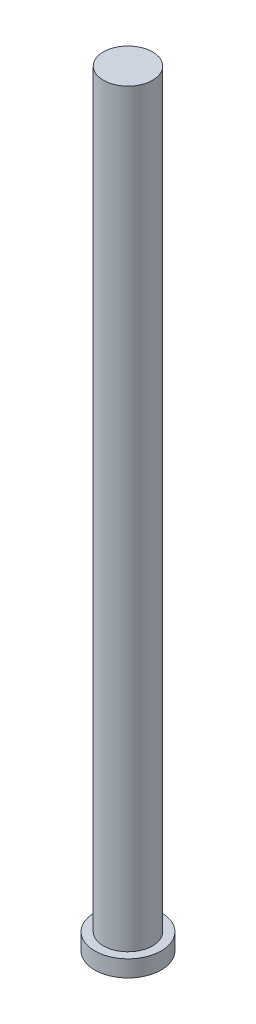
SolidWorks part; units mm, degrees
ref_plane "Front Plane" through (0, 0, 0) normal (0, 0, 1) x (1, 0, 0)
ref_plane "Top Plane" through (0, 0, 0) normal (0, 1, 0) x (1, 0, 0)
ref_plane "Right Plane" through (0, 0, 0) normal (1, 0, 0) x (0, 0, -1)
sketch "Sketch1" plane through (0, 0, 0) normal (0, 1, 0) x (1, 0, 0)
  circle A0 centre (0, 0) radius 6.35
  dimension "D1" = 12.7
extrude "Boss-Extrude1" add sketch "Sketch1" against normal blind 3.175
sketch "Sketch2" plane through (0, 0, 0) normal (0, 1, 0) x (1, 0, 0)
  circle A0 centre (0, 0) radius 4.699
  dimension "D1" = 9.398
extrude "Boss-Extrude2" add sketch "Sketch2" along normal blind 143.256
hole_wizard "#97 (0.0059) Diameter Hole1" positions "3DSketch1" profile "Sketch3" hole size "#97" standard "ANSI Inch"
sketch3d "3DSketch1"
  line L0 (0, -3.175, 0) -> (0, 0, 0) construction
  point P0 (0, -3.175, 0)
sketch "Sketch3" plane through (0, -3.175, 0) normal (1, 0, 0) x (0, 0, -1)
  line L0 (0, 0) -> (0, 143.256)
  line L1 (0, 143.256) -> (3.175, 143.256)
  line L2 (3.175, 143.256) -> (3.175, 0)
  line L5 (3.175, 0) -> (0, 0)
  line L10 (0, 143.256) -> (-3.175, 143.256) construction
  line L11 (0, -6.35) -> (0, 107.95) construction
  dimension "Hole Dia." = 6.35
  dimension "Hole Depth" = 143.256
  dimension "Drill Angle" = 180
